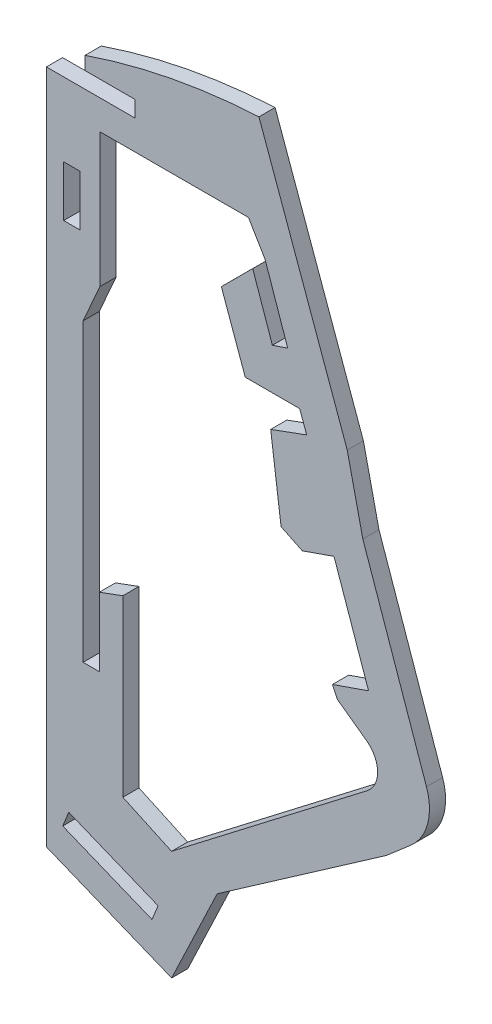
SolidWorks part; units mm, degrees
ref_plane "Front" through (0, 0, 0) normal (0, 0, 1) x (1, 0, 0)
ref_plane "Top" through (0, 0, 0) normal (0, 1, 0) x (1, 0, 0)
ref_plane "Right" through (0, 0, 0) normal (1, 0, 0) x (0, 0, -1)
sketch "Sketch1" plane through (0, 0, 0) normal (0, 0, 1) x (1, 0, 0)
  line L0 (1079.8769, -44.1052) -> (1068.0562, -10.173)
  line L8 (1065.1575, 2.6968) -> (1048.7596, 48.1016)
  line L9 (1019.2139, 30.9259) -> (1019.2139, 6.0188)
  line L10 (1019.2139, 6.0188) -> (1016.1001, -1.0389)
  line L11 (1016.1001, -55.9767) -> (1016.1001, -1.0389)
  line L12 (1016.1001, -55.9767) -> (1019.1001, -55.9767)
  line L13 (1019.1001, -55.9767) -> (1019.1001, -43.1981)
  line L14 (1019.1001, -43.1981) -> (1023.4786, -41.5804)
  line L15 (1023.4786, -41.5804) -> (1023.4786, -73.9921)
  line L16 (1023.4786, -73.9921) -> (1032.5266, -78.167)
  line L17 (1032.5266, -78.167) -> (1068.8505, -50.2583)
  line L18 (1065.1575, 2.6968) -> (1068.0562, -10.173)
  line L21 (1068.7348, -42.2424) -> (1063.3251, -38.329)
  line L22 (1063.3251, -38.329) -> (1062.4074, -36.386)
  line L23 (1062.4074, -36.386) -> (1069.1157, -34.0491)
  line L24 (1069.1157, -34.0491) -> (1062.7007, -15.6345)
  line L25 (1062.7007, -15.6345) -> (1056.8103, -17.6865)
  line L26 (1056.8103, -17.6865) -> (1052.8696, -15.7793)
  line L27 (1052.8696, -15.7793) -> (1050.9415, -1.0831)
  line L28 (1050.9415, -1.0831) -> (1057.6251, 1.3621)
  line L29 (1057.6251, 1.3621) -> (1056.321, 4.9484)
  line L30 (1056.321, 4.9484) -> (1046.2142, 4.9484)
  line L31 (1046.2142, 4.9484) -> (1041.7732, 17.2945)
  line L32 (1041.7732, 17.2945) -> (1047.6008, 23.112)
  line L33 (1047.6008, 23.112) -> (1051.2538, 12.6056)
  line L34 (1051.2538, 12.6056) -> (1054.1003, 13.5528)
  line L35 (1054.1003, 13.5528) -> (1049.9091, 25.7207)
  line L36 (1049.9091, 25.7207) -> (1046.8163, 30.9399)
  line L37 (1046.8163, 30.9399) -> (1019.2139, 30.9259)
  line L38 (1072.4404, -58.8762) -> (1040.9911, -80.7703)
  line L39 (1040.9911, -80.7703) -> (1032.5435, -98.5367)
  line L40 (1032.5435, -98.5367) -> (1009.2795, -89.074)
  line L41 (1009.2795, -89.074) -> (1009.2795, 36.3926)
  line L42 (1012.3078, -84.2073) -> (1013.4382, -81.4283)
  line L43 (1013.4382, -81.4283) -> (1030.0254, -88.1752)
  line L44 (1030.0254, -88.1752) -> (1028.895, -90.9542)
  line L45 (1028.895, -90.9542) -> (1012.3078, -84.2073)
  line L48 (1076.9711, -54.962) -> (1072.4404, -58.8762)
  line L49 (1035.7261, 39.3926) -> (1016.4663, 39.3926)
  line L50 (1035.7261, 36.3926) -> (1009.2795, 36.3926)
  line L56 (1015.483, 22.7319) -> (1015.483, 13.2819)
  line L57 (1015.483, 13.2819) -> (1012.483, 13.2819)
  line L58 (1012.483, 13.2819) -> (1012.483, 22.7319)
  line L59 (1012.483, 22.7319) -> (1015.483, 22.7319)
  line L60 (1016.4663, 41.8487) -> (1016.4663, 39.3926)
  line L61 (1035.7261, 39.3926) -> (1035.7261, 36.3926)
  arc A0 (1076.9711, -54.962) -> (1079.8769, -44.1052) centre (1070.4335, -47.3949) ccw
  arc A1 (1068.7348, -42.2424) -> (1068.8505, -50.2583) centre (1065.8042, -46.2935) cw
  arc A2 (1016.4663, 41.8487) -> (1048.7596, 48.1016) centre (1054.9098, -70.1773) cw
  dimension "D10" = 5
  dimension "D12" = 10
  dimension "D1" = 90
  dimension "D2" = 90
  dimension "D3" = 9.45
  dimension "D4" = 90
  dimension "D5" = 3
  dimension "D6" = 3
  dimension "D7" = 90
  dimension "D8" = 3
  dimension "D9" = 3
  dimension "D11" = 90
  dimension "D13" = 90
  dimension "D14" = 90
  dimension "D15" = 19.5
extrude "Base-Extrude" add sketch "Sketch1" along normal blind 3
sketch "Sketch2" plane through (0, 0, 3) normal (0, 0, 1) x (1, 0, 0)
  line L0 (1035.7261, 39.3926) -> (1035.7261, 36.3926)
  line L1 (1035.7261, 36.3926) -> (1025.7261, 36.3926)
  line L3 (1025.7261, 36.3926) -> (1025.7261, 39.3926)
  line L5 (1025.7261, 39.3926) -> (1035.7261, 39.3926)
  dimension "D1" = 10
extrude "Boss-Extrude1" add sketch "Sketch2" against normal blind 3
